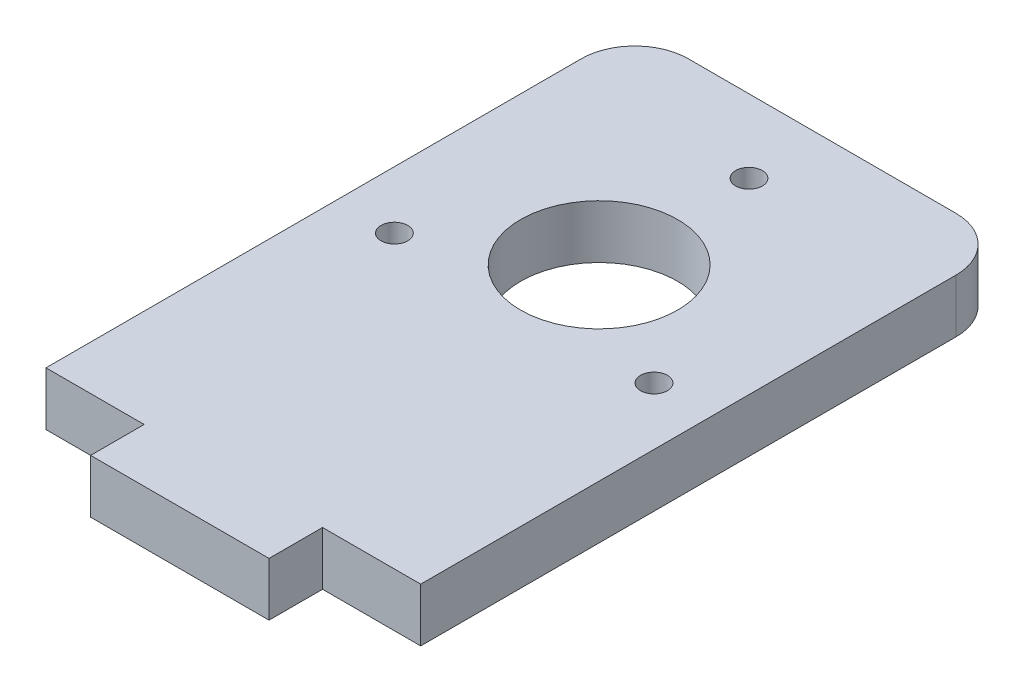
SolidWorks part; units mm, degrees
ref_plane "Plan de face" through (0, 0, 0) normal (0, 0, 1) x (1, 0, 0)
ref_plane "Plan de dessus" through (0, 0, 0) normal (0, 1, 0) x (1, 0, 0)
ref_plane "Plan de droite" through (0, 0, 0) normal (1, 0, 0) x (0, 0, -1)
sketch "Esquisse1" plane through (0, 0, 0) normal (0, 1, 0) x (1, 0, 0)
  line L0 (-10.5, 3) -> (-5, 3)
  line L1 (-7.5, 36) -> (7.5, 36)
  line L2 (-10.5, 33) -> (-10.5, 3)
  line L3 (-5, 0) -> (5, 0)
  line L4 (10.5, 33) -> (10.5, 3)
  line L5 (-5, 3) -> (-5, 0)
  line L6 (5, 0) -> (5, 3)
  line L7 (5, 3) -> (10.5, 3)
  line L8 (0, 0) -> (0, 36) construction
  circle A0 centre (0, 23.5) radius 4.4
  circle A1 centre (0, 31.9) radius 0.75
  circle A2 centre (7.2746, 19.3) radius 0.75
  circle A3 centre (-7.2746, 19.3) radius 0.75
  arc A4 (7.5, 36) -> (10.5, 33) centre (7.5, 33) cw
  arc A5 (-7.5, 36) -> (-10.5, 33) centre (-7.5, 33) ccw
  point P4 (0, 0)
  point P17 (6.3528, 17.7712)
  point P18 (0, 23.5)
  point P22 (0, 23.5)
  point P25 (10.5, 36)
  point P28 (-10.5, 36)
  dimension "D5" = 8.8
  dimension "D7" = 8.4
  dimension "D8" = 1.5
  dimension "D10" = 3
  dimension "D1" = 36
  dimension "D2" = 21
  dimension "D3" = 10
  dimension "D4" = 3
  dimension "D6" = 12.5
  dimension "D9" = 3
extrude "Boss.-Extru.1" add sketch "Esquisse1" along normal blind 3
